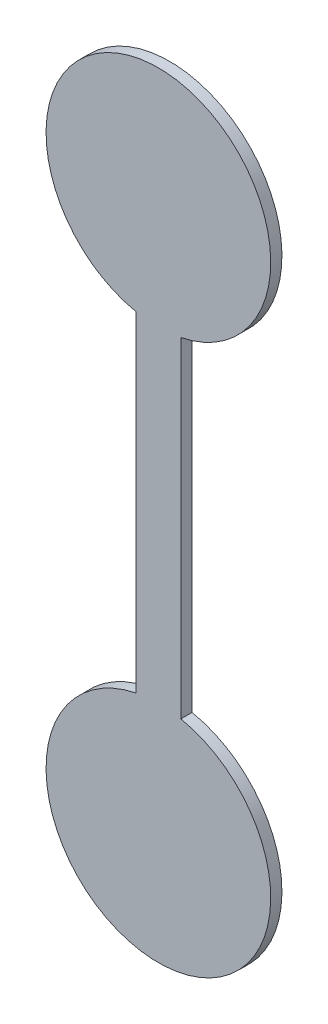
SolidWorks part; units mm, degrees
ref_plane "Front Plane" through (0, 0, 0) normal (0, 0, 1) x (1, 0, 0)
ref_plane "Top Plane" through (0, 0, 0) normal (0, 1, 0) x (1, 0, 0)
ref_plane "Right Plane" through (0, 0, 0) normal (1, 0, 0) x (0, 0, -1)
sketch "Sketch1" plane through (0, 0, 0) normal (0, 0, 1) x (1, 0, 0)
  line L0 (0, 0) -> (0, 490) construction
  line L1 (-20, 0) -> (-20, 490)
  line L2 (20, 0) -> (20, 490)
  circle A0 centre (0, 0) radius 100
  circle A1 centre (0, 490) radius 100
  arc A2 (-20, 0) -> (20, 0) centre (0, 0) ccw
  arc A3 (20, 490) -> (-20, 490) centre (0, 490) ccw
  point P5 (0, 245)
  dimension "D1" = 200
  dimension "D2" = 20
  dimension "D3" = 490
extrude "Boss-Extrude1" add sketch "Sketch1" along normal mid plane 10 contours A3 L2 A1 L1 | A2 L1 A0 L2
